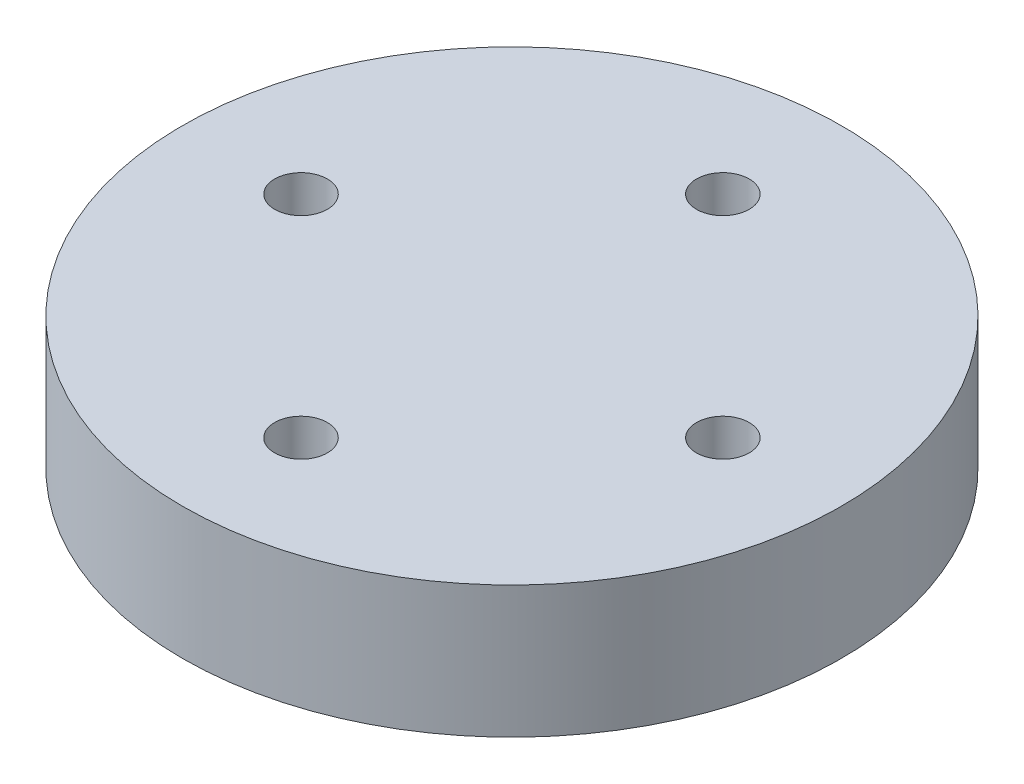
SolidWorks part; units mm, degrees
ref_plane "Front Plane" through (0, 0, 0) normal (0, 0, 1) x (1, 0, 0)
ref_plane "Top Plane" through (0, 0, 0) normal (0, 1, 0) x (1, 0, 0)
ref_plane "Right Plane" through (0, 0, 0) normal (1, 0, 0) x (0, 0, -1)
sketch "Sketch1" plane through (0, 0, 0) normal (0, 1, 0) x (1, 0, 0)
  circle A0 centre (0, 0) radius 12.5
  dimension "D1" = 25
extrude "Boss-Extrude1" add sketch "Sketch1" along normal blind 5
sketch "Sketch2" plane through (0, 5, 0) normal (0, 1, 0) x (1, 0, 0)
  line L0 (0, 12.5) -> (0, -12.5) construction
  circle A0 centre (0, 0) radius 12.5 construction
  circle A1 centre (0, 8) radius 1
  circle A2 centre (8, 0) radius 1
  circle A3 centre (0, -8) radius 1
  circle A4 centre (-8, 0) radius 1
  point P17 (0, 0)
  dimension "D1" = 2
  dimension "D2" = 8
  dimension "D3" = 4
extrude "Cut-Extrude1" cut sketch "Sketch2" against normal through all
sketch "Sketch3" plane through (0, 5, 0) normal (0, 1, 0) x (1, 0, 0)
  circle A0 centre (0, 0) radius 5.2632
